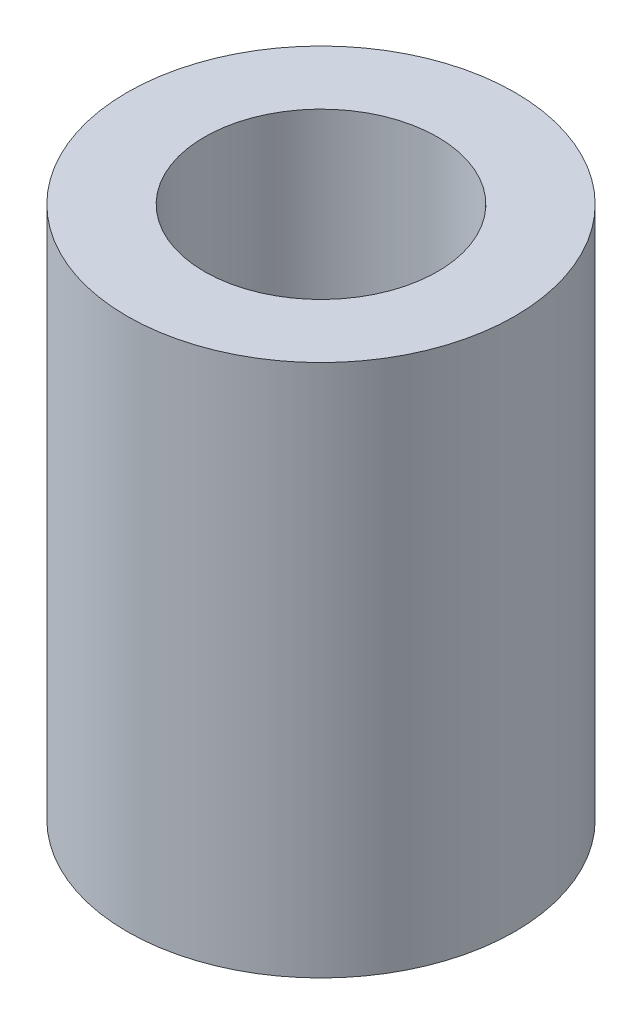
SolidWorks part; units mm, degrees
ref_plane "Front Plane" through (0, 0, 0) normal (0, 0, 1) x (1, 0, 0)
ref_plane "Top Plane" through (0, 0, 0) normal (0, 1, 0) x (1, 0, 0)
ref_plane "Right Plane" through (0, 0, 0) normal (1, 0, 0) x (0, 0, -1)
sketch "Sketch1" plane through (0, 0, 0) normal (0, 1, 0) x (1, 0, 0)
  circle A0 centre (0, 0) radius 1.75
  circle A1 centre (0, 0) radius 2.91
  dimension "D1" = 3.5
  dimension "D2" = 5.82
extrude "Boss-Extrude1" add sketch "Sketch1" along normal blind 8
